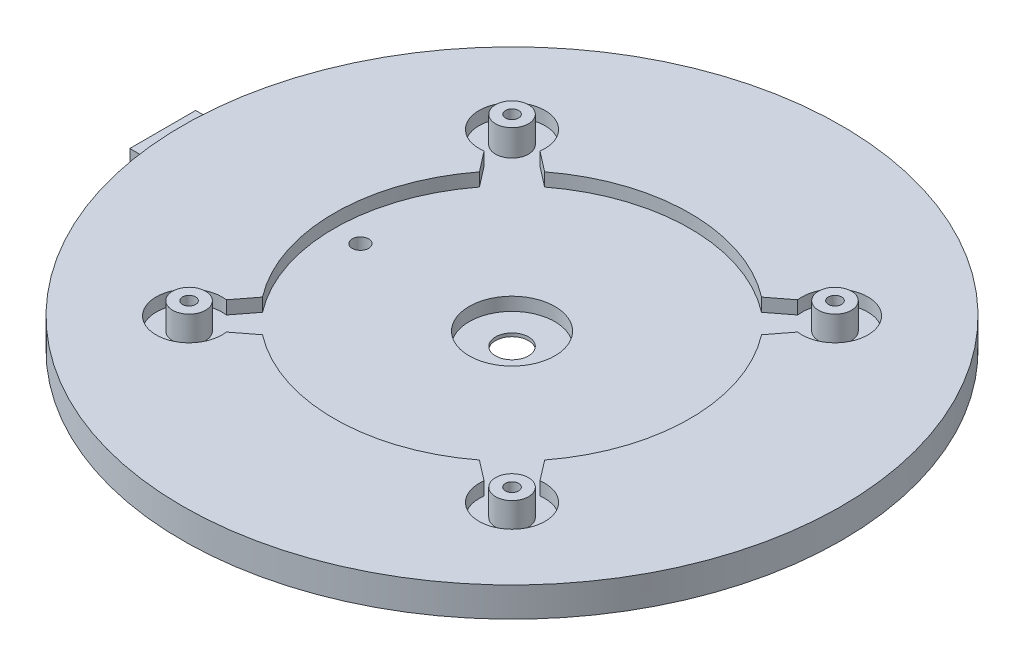
SolidWorks part; units mm, degrees
ref_plane "Front Plane" through (0, 0, 0) normal (0, 0, 1) x (1, 0, 0)
ref_plane "Top Plane" through (0, 0, 0) normal (0, 1, 0) x (1, 0, 0)
ref_plane "Right Plane" through (0, 0, 0) normal (1, 0, 0) x (0, 0, -1)
sketch "Sketch1" plane through (0, 0, 0) normal (0, 1, 0) x (1, 0, 0)
  circle A0 centre (0, 0) radius 50
  dimension "D1" = 100
extrude "Boss-Extrude1" add sketch "Sketch1" along normal blind 4.5 contours A0
sketch "Sketch3" plane through (0, 0, 0) normal (0, 0, 1) x (1, 0, 0)
  line L0 (0, 2.5) -> (-53, 2.5)
  line L1 (-53, 2.5) -> (-53, -2.25)
  line L2 (-50.5, -2.25) -> (-50.5, 0)
  line L3 (-50.5, 0) -> (0, 0)
  line L4 (0, 0) -> (0, 2.5)
  line L5 (-50, 4.5) -> (-50, 0) construction
  line L6 (-50, 0) -> (50, 0) construction
  arc A0 (-53, -2.25) -> (-50.5, -2.25) centre (-51.75, -2.25) ccw
  dimension "D3" = 1.25
  dimension "D1" = 0.5
  dimension "D2" = 4.75
  dimension "D4" = 3.5
extrude "Boss-Extrude2" add sketch "Sketch3" along normal mid plane 10
sketch "Sketch4" plane through (0, 0, 0) normal (0, -1, 0) x (1, 0, 0)
  circle A0 centre (0, 0) radius 18
  dimension "D1" = 36
extrude "Extrude-Thin1" add sketch "Sketch4" along normal blind 5 thin thin type one direction reverse wall 2
sketch "Sketch7" plane through (0, 4.5, 0) normal (0, 1, 0) x (1, 0, 0)
  circle A0 centre (0, 0) radius 27
  dimension "54" = 54
extrude "Cut-Extrude1" cut sketch "Sketch7" against normal blind 2
hole_wizard "CBORE for M5 Hex Head Bolt2" positions "Sketch8" profile "Sketch9" counterbore size "M5" standard "ANSI Metric" end condition through all
sketch "Sketch8" plane through (0, 2.5, 0) normal (0, 1, 0) x (1, 0, 0)
  point P0 (0, 0)
sketch "Sketch9" plane through (0, 2.5, 0) normal (1, 0, 0) x (0, 0, 1)
  line L0 (0, 0) -> (0, 7.5)
  line L1 (0, 7.5) -> (2.5, 7.5)
  line L3 (2.5, 7.5) -> (2.5, 2)
  line L4 (2.5, 2) -> (6.5, 2)
  line L5 (6.5, 2) -> (6.5, 0)
  line L7 (6.5, 0) -> (0, 0)
  line L11 (0, -6.35) -> (0, 107.95) construction
  dimension "Thru Hole Dia." = 5
  dimension "Thru Hole Depth" = 7.5
  dimension "C'Bore Dia." = 13
  dimension "C'Bore Depth" = 2
sketch "Sketch10" plane through (0, 2.5, 0) normal (0, 1, 0) x (1, 0, 0)
  line L0 (-36.4898, 0) -> (0, 0) construction
  line L1 (0, 0) -> (0, 38.1774) construction
  line L2 (0, 0) -> (-29.9205, 29.9205) construction
  line L3 (-21.4057, 16.4559) -> (-23.7929, 19.5503)
  line L4 (-16.4559, 21.4057) -> (-19.5503, 23.7929)
  arc A0 (-19.5503, 23.7929) -> (-23.7929, 19.5503) centre (-24.5, 24.5) ccw
  arc A1 (-16.4559, 21.4057) -> (-21.4057, 16.4559) centre (0, 0) ccw
  circle A6 centre (0, 0) radius 27 construction
  circle A7 centre (0, 0) radius 27 construction
  dimension "D2" = 59
  dimension "D3" = 10
  dimension "D1" = 45
  dimension "D4" = 6
  dimension "D5" = 7
extrude "Cut-Extrude2" cut sketch "Sketch10" along normal through all
sketch "Sketch11" plane through (0, 2.5, 0) normal (0, 1, 0) x (1, 0, 0)
  circle A0 centre (-24.5, 24.5) radius 2.5
  dimension "D1" = 5
extrude "Boss-Extrude3" add sketch "Sketch11" along normal blind 4
sketch "Sketch12" plane through (0, 6.5, 0) normal (0, 1, 0) x (1, 0, 0)
  circle A0 centre (-24.5, 24.5) radius 1
  dimension "D1" = 2
extrude "Cut-Extrude3" cut sketch "Sketch12" against normal through all
sketch "Sketch13" plane through (0, -5, 0) normal (0, -1, 0) x (1, 0, 0)
  line L0 (-19.5926, 0) -> (0, 0) construction
  line L1 (0, 0) -> (0, 21.368) construction
  circle A0 centre (-14, 0) radius 2.5
  dimension "D2" = 5
  dimension "D1" = 28
extrude "Extrude-Thin2" add sketch "Sketch13" against normal up to next thin thin type one direction reverse wall 1
pattern_circular "CirPattern1" count 4 over 360 about axis through (0, 0, 0) along (0, 1, 0) of "Cut-Extrude2", "Boss-Extrude3", "Cut-Extrude3", "Extrude-Thin2"
sketch "Sketch14" plane through (0, 2.5, 0) normal (0, 1, 0) x (1, 0, 0)
  circle A0 centre (-23, 0) radius 1.25
  dimension "D1" = 2.5
  dimension "D2" = 23
extrude "Cut-Extrude4" cut sketch "Sketch14" against normal through all
